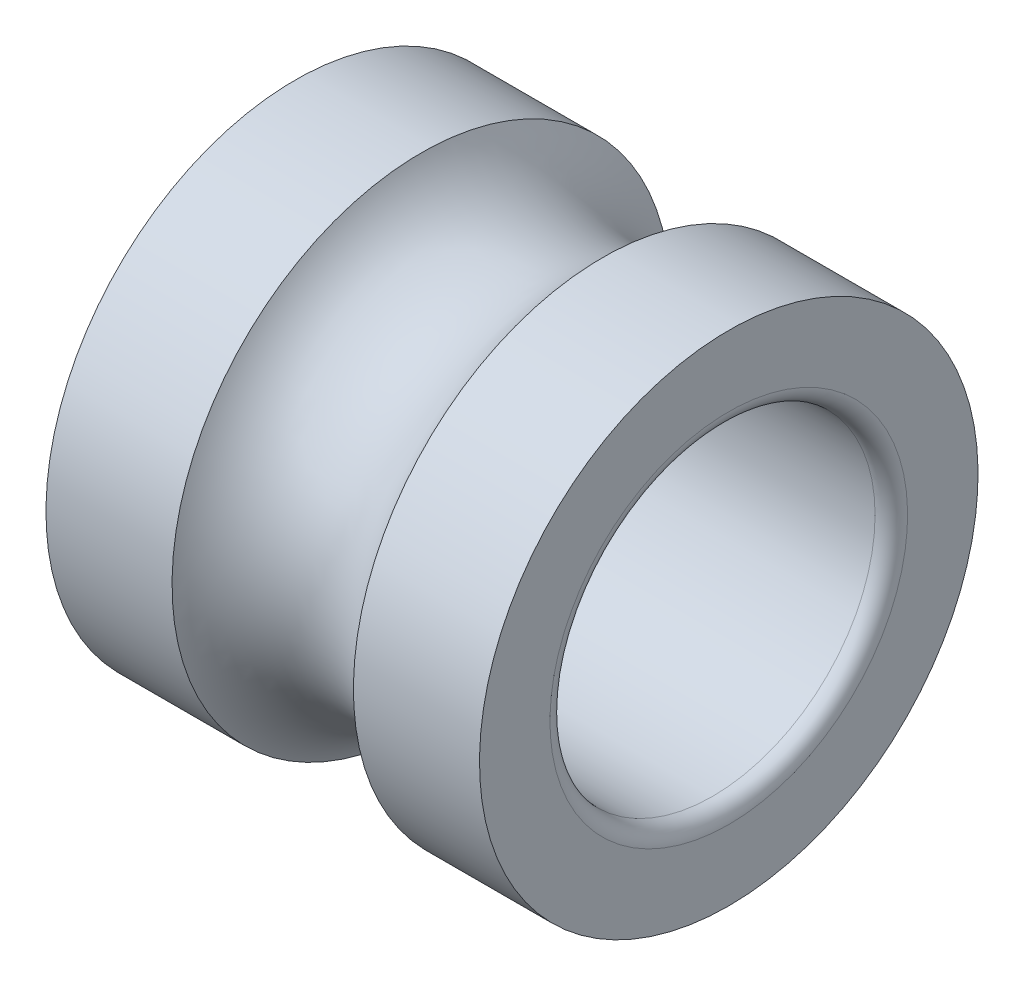
SolidWorks part; units mm, degrees
ref_plane "Plan de face" through (0, 0, 0) normal (0, 0, 1) x (1, 0, 0)
ref_plane "Plan de dessus" through (0, 0, 0) normal (0, 1, 0) x (1, 0, 0)
ref_plane "Plan de droite" through (0, 0, 0) normal (1, 0, 0) x (0, 0, -1)
sketch "Esquisse1" plane through (0, 0, 0) normal (0, 0, 1) x (1, 0, 0)
  line L0 (2, 4) -> (2, 1.5) construction
  line L1 (0.15, 4) -> (3.85, 4) construction
  line L2 (0, 3.85) -> (0, 1.65) construction
  line L3 (0.15, 1.5) -> (3.85, 1.5)
  line L4 (4, 3.85) -> (4, 1.65) construction
  line L5 (4, 3.2) -> (0, 3.2) construction
  line L6 (4, 2.3) -> (2.8367, 2.3)
  line L7 (0, 0) -> (4, 0) construction
  line L8 (4, 2.3) -> (4, 1.65)
  line L9 (0, 2.3) -> (0, 1.65)
  line L10 (1.1633, 2.3) -> (0, 2.3)
  arc A1 (0, 1.65) -> (0.15, 1.5) centre (0.15, 1.65) ccw
  arc A2 (0.15, 4) -> (0, 3.85) centre (0.15, 3.85) ccw construction
  arc A3 (4, 3.85) -> (3.85, 4) centre (3.85, 3.85) ccw construction
  arc A4 (3.85, 1.5) -> (4, 1.65) centre (3.85, 1.65) ccw
  arc A5 (1.1633, 2.3) -> (2.8367, 2.3) centre (2, 2.75) ccw
  dimension "D4" = 0.15
  dimension "D5" = 1.9
  dimension "D1" = 1.5
  dimension "D2" = 4
  dimension "D3" = 4
  dimension "D6" = 2.3
  dimension "D7" = 3.2
revolve "Révolution1" add sketch "Esquisse1" angle 360 about L7
